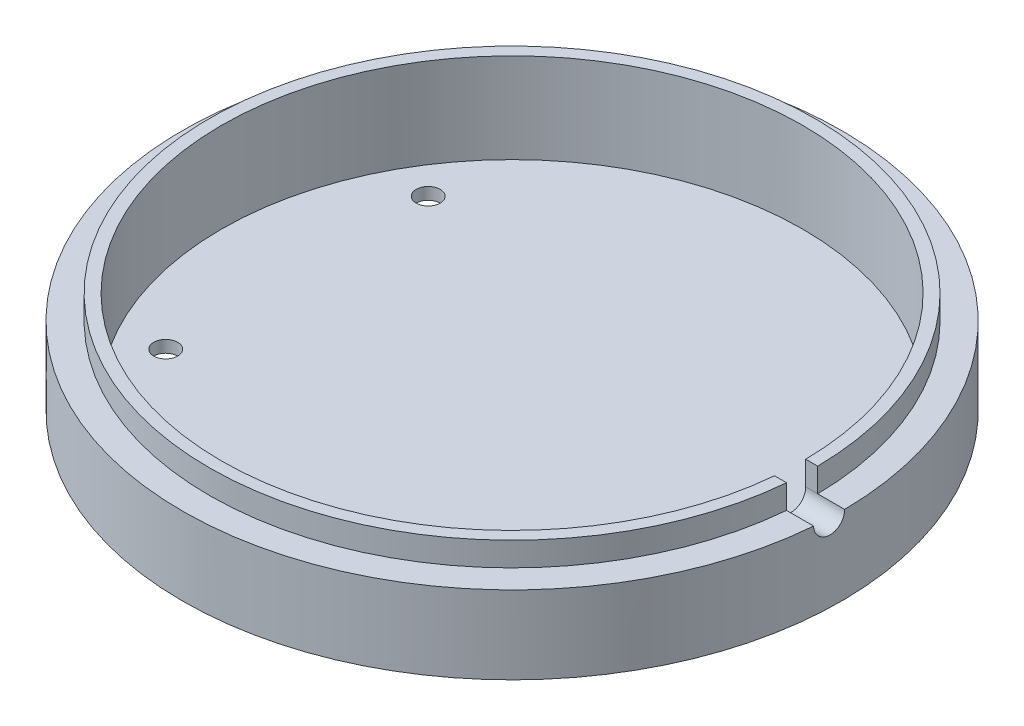
SolidWorks part; units mm, degrees
ref_plane "Front Plane" through (0, 0, 0) normal (0, 0, 1) x (1, 0, 0)
ref_plane "Top Plane" through (0, 0, 0) normal (0, 1, 0) x (1, 0, 0)
ref_plane "Right Plane" through (0, 0, 0) normal (1, 0, 0) x (0, 0, -1)
sketch "Sketch2" plane through (0, 0, 0) normal (0, 1, 0) x (1, 0, 0)
  circle A0 centre (0, 0) radius 55
  circle A1 centre (0, 0) radius 52.5
  dimension "D1" = 110
  dimension "D2" = 105
extrude "Boss-Extrude2" add sketch "Sketch2" along normal blind 13 contours A0
sketch "Sketch3" plane through (0, 0, 0) normal (0, -1, 0) x (1, 0, 0)
  circle A0 centre (0, 0) radius 52.5
  dimension "D1" = 105
sketch "Sketch7" plane through (0, 13, 0) normal (0, 1, 0) x (1, 0, 0)
  circle A0 centre (0, 0) radius 50.5
  dimension "D1" = 101
extrude "Boss-Extrude3" add sketch "Sketch7" along normal blind 4
sketch "Sketch8" plane through (0, 17, 0) normal (0, 1, 0) x (1, 0, 0)
  circle A0 centre (0, 0) radius 48.5
  dimension "D1" = 97
extrude "Cut-Extrude3" cut sketch "Sketch8" against normal blind 15
sketch "Sketch9" plane through (0, 2, 0) normal (0, 1, 0) x (1, 0, 0)
  line L1 (-38, -24) -> (38, -24)
  line L2 (-38, -24) -> (-38, 24)
  line L3 (-38, 24) -> (38, 24)
  line L4 (38, -24) -> (38, 24)
  line L5 (36, -2.1049) -> (39.1627, -2.1049)
  line L6 (36, -2.1049) -> (36, 0.5)
  line L7 (36, 0.5) -> (39.1627, 0.5)
  line L8 (39.1627, -2.1049) -> (39.1627, 0.5)
  circle A0 centre (-35.8, -22) radius 2
  circle A1 centre (36, -22) radius 2
  circle A2 centre (36, 22) radius 2
  circle A3 centre (-36, 22) radius 2
  dimension "D5" = 4
  dimension "D6" = 4
  dimension "D7" = 4
  dimension "D8" = 4
  dimension "D1" = 76
  dimension "D2" = 38
  dimension "D3" = 48
  dimension "D4" = 24
  dimension "D9" = 2.2
  dimension "D10" = 2
  dimension "D11" = 2
  dimension "D12" = 2
  dimension "D13" = 2
  dimension "D14" = 2
  dimension "D15" = 21.5
extrude "Cut-Extrude4" cut sketch "Sketch9" against normal blind 15 contours A1 | A3 | A0 | A2 | L6 L5 L8 L7
sketch "Sketch10" plane through (36, 0, 0) normal (1, 0, 0) x (0, 0, -1)
  line L2 (0.5, 0) -> (0.5, 2) construction
  line L5 (55, 13) -> (-55, 13) construction
  circle A2 centre (-2, 13) radius 2.5
  dimension "D1" = 5
  dimension "D2" = 2.5
  dimension "D3" = 0
extrude "Cut-Extrude5" cut sketch "Sketch10" against normal blind 1 and the other way blind 20
sketch "Sketch11" plane through (0, 2, 0) normal (0, 1, 0) x (1, 0, 0)
  line L1 (40.3308, -4.078) -> (34.0566, -4.078)
  line L2 (40.3308, -4.078) -> (40.3308, 3.3016)
  line L3 (40.3308, 3.3016) -> (34.0566, 3.3016)
  line L4 (34.0566, -4.078) -> (34.0566, 3.3016)
sketch "Sketch12" plane through (0, 0, 0) normal (0, -1, 0) x (-1, 0, 0)
  line L1 (-32.0049, 3.5231) -> (-42.9913, 3.5231)
  line L2 (-32.0049, 3.5231) -> (-32.0049, -4.6945)
  line L3 (-32.0049, -4.6945) -> (-42.9913, -4.6945)
  line L4 (-42.9913, 3.5231) -> (-42.9913, -4.6945)
extrude "Boss-Extrude5" add sketch "Sketch11" along normal blind 0.01 and the other way blind 2
sketch3d "3DSketch1" plane through (0, 0, 0) normal (0, 0, 1) x (1, 0, 0)
sketch3d "3DSketch2" plane through (0, 0, 0) normal (0, 0, 1) x (1, 0, 0)
  dimension "D1" = 10
sketch "Sketch13" plane through (0, 0, 0) normal (1, 0, 0) x (0, 0, -1)
  line L1 (-4.5, 13) -> (0.5, 13)
  line L2 (-4.5, 13) -> (-4.5, 19.1151)
  line L3 (-4.5, 19.1151) -> (0.5, 19.1151)
  line L4 (0.5, 13) -> (0.5, 19.1151)
extrude "Cut-Extrude6" cut sketch "Sketch13" along normal up to surface (50.2991 mm away)
